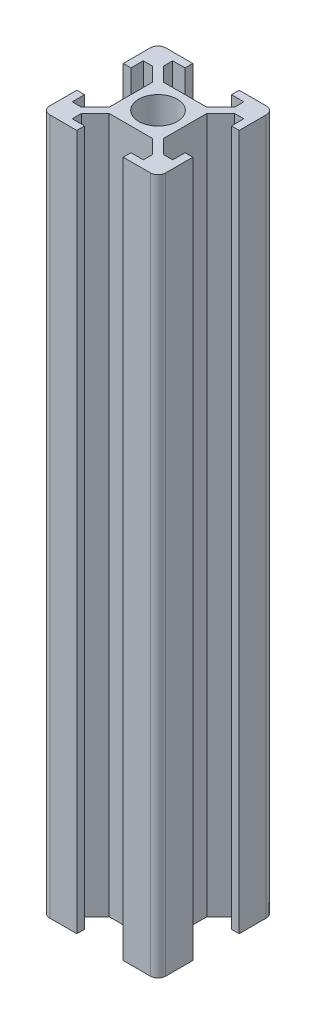
SolidWorks part; units mm, degrees
ref_plane "Front Plane" through (0, 0, 0) normal (0, 0, 1) x (1, 0, 0)
ref_plane "Top Plane" through (0, 0, 0) normal (0, 1, 0) x (1, 0, 0)
ref_plane "Right Plane" through (0, 0, 0) normal (1, 0, 0) x (0, 0, -1)
sketch "Sketch1" plane through (0, 0, 0) normal (0, 1, 0) x (1, 0, 0)
  line L0 (-7.5, -3) -> (-7.5, -6.5)
  line L5 (-6.5, -7.5) -> (-3, -7.5)
  line L6 (-7.5, -3) -> (-6.5, -3)
  line L7 (-3, -7.5) -> (-3, -6.5)
  line L8 (-6.5, -3) -> (-6.5, -4.6)
  line L9 (-3, -6.5) -> (-4.6, -6.5)
  line L10 (-6.5, -4.6) -> (-5.3071, -4.6)
  line L11 (-4.6, -6.5) -> (-4.6, -5.3071)
  line L13 (-3.5071, 0) -> (-3.5071, -2.8)
  line L14 (-3.5071, -2.8) -> (-5.3071, -4.6)
  line L16 (0, -3.5071) -> (-2.8, -3.5071)
  line L17 (-2.8, -3.5071) -> (-4.6, -5.3071)
  line L18 (-3.5071, 2.8) -> (-5.3071, 4.6)
  line L19 (-6.5, 4.6) -> (-5.3071, 4.6)
  line L20 (-6.5, 3) -> (-6.5, 4.6)
  line L21 (-7.5, 3) -> (-6.5, 3)
  line L22 (-7.5, 6.5) -> (-7.5, 3)
  line L23 (-3, 7.5) -> (-6.5, 7.5)
  line L24 (-3, 7.5) -> (-3, 6.5)
  line L25 (-3, 6.5) -> (-4.6, 6.5)
  line L26 (-4.6, 6.5) -> (-4.6, 5.3071)
  line L27 (-2.8, 3.5071) -> (-4.6, 5.3071)
  line L28 (0, 3.5071) -> (-2.8, 3.5071)
  line L31 (-3.5071, 0) -> (-3.5071, 2.8)
  line L32 (2.8, 3.5071) -> (4.6, 5.3071)
  line L33 (4.6, 6.5) -> (4.6, 5.3071)
  line L34 (3, 6.5) -> (4.6, 6.5)
  line L35 (3, 7.5) -> (3, 6.5)
  line L36 (6.5, 7.5) -> (3, 7.5)
  line L37 (7.5, 3) -> (7.5, 6.5)
  line L38 (7.5, 3) -> (6.5, 3)
  line L39 (6.5, 3) -> (6.5, 4.6)
  line L40 (6.5, 4.6) -> (5.3071, 4.6)
  line L41 (3.5071, 2.8) -> (5.3071, 4.6)
  line L42 (3.5071, 0) -> (3.5071, 2.8)
  line L45 (0, 3.5071) -> (2.8, 3.5071)
  line L46 (3.5071, -2.8) -> (5.3071, -4.6)
  line L47 (6.5, -4.6) -> (5.3071, -4.6)
  line L48 (6.5, -3) -> (6.5, -4.6)
  line L49 (7.5, -3) -> (6.5, -3)
  line L50 (7.5, -6.5) -> (7.5, -3)
  line L51 (3, -7.5) -> (6.5, -7.5)
  line L52 (3, -7.5) -> (3, -6.5)
  line L53 (3, -6.5) -> (4.6, -6.5)
  line L54 (4.6, -6.5) -> (4.6, -5.3071)
  line L55 (2.8, -3.5071) -> (4.6, -5.3071)
  line L56 (0, -3.5071) -> (2.8, -3.5071)
  line L59 (3.5071, 0) -> (3.5071, -2.8)
  arc A1 (-6.5, -7.5) -> (-7.5, -6.5) centre (-6.5, -6.5) cw
  arc A2 (-2.5, 0) -> (0, -2.5) centre (0, 0) ccw
  arc A3 (-7.5, 6.5) -> (-6.5, 7.5) centre (-6.5, 6.5) cw
  arc A4 (0, 2.5) -> (-2.5, 0) centre (0, 0) ccw
  arc A5 (6.5, 7.5) -> (7.5, 6.5) centre (6.5, 6.5) cw
  arc A6 (2.5, 0) -> (0, 2.5) centre (0, 0) ccw
  arc A7 (7.5, -6.5) -> (6.5, -7.5) centre (6.5, -6.5) cw
  arc A8 (0, -2.5) -> (2.5, 0) centre (0, 0) ccw
  point P8 (-7.5, -3)
  point P9 (-3, -7.5)
  point P75 (0, 0)
  dimension "D1" = 1
  dimension "D9" = 2.5
  dimension "D2" = 3
  dimension "D3" = 7.5
  dimension "D4" = 3
  dimension "D5" = 1
  dimension "D6" = 1
  dimension "D7" = 1.6
  dimension "D8" = 2.8
  dimension "D10" = 1
  dimension "D11" = 4
extrude "Boss-Extrude1" add sketch "Sketch1" along normal blind 90
